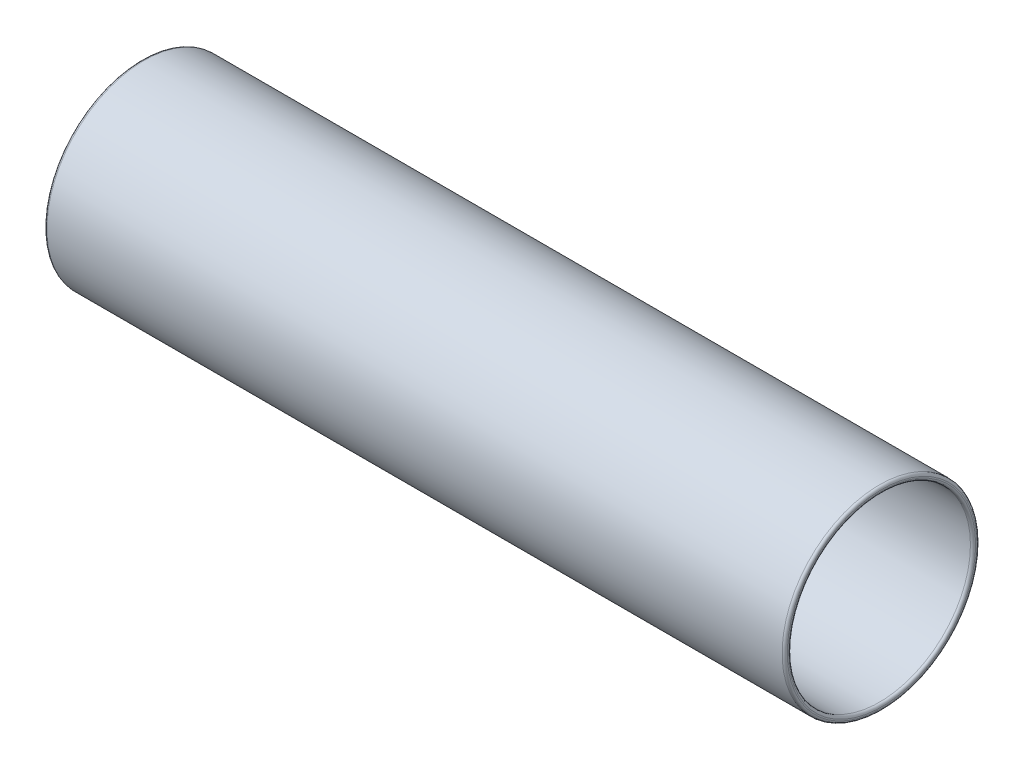
SolidWorks part; units mm, degrees
material "1060-H12"
ref_plane "Płaszczyzna przednia" through (0, 0, 0) normal (0, 0, 1) x (1, 0, 0)
ref_plane "Płaszczyzna górna" through (0, 0, 0) normal (0, 1, 0) x (1, 0, 0)
ref_plane "Płaszczyzna prawa" through (0, 0, 0) normal (1, 0, 0) x (0, 0, -1)
sketch "Szkic1" plane through (0, 0, 0) normal (0, 0, 1) x (1, 0, 0)
  line L0 (0, 0) -> (105558.8307, 0) construction
  line L1 (-158.6842, 75) -> (411.3158, 75)
  line L2 (-158.6842, 75) -> (-158.6842, 0)
  line L3 (411.3158, 75) -> (411.3158, 0)
  line L4 (-158.6842, 70) -> (411.3158, 70)
  dimension "D1" = 150
  dimension "D2" = 140
  dimension "D3" = 570
revolve "Obrót1" add sketch "Szkic1" angle 360 about L0
fillet "Zaokrąglenie1" radius 2 4 edges at (411.3158, 0, 70) (411.3158, 0, 75) (-158.6842, 0, 70) (-158.6842, 0, 75)
cosmetic thread "Oznaczenie gwintu1" parameters "D1"=20, "D2"=149
